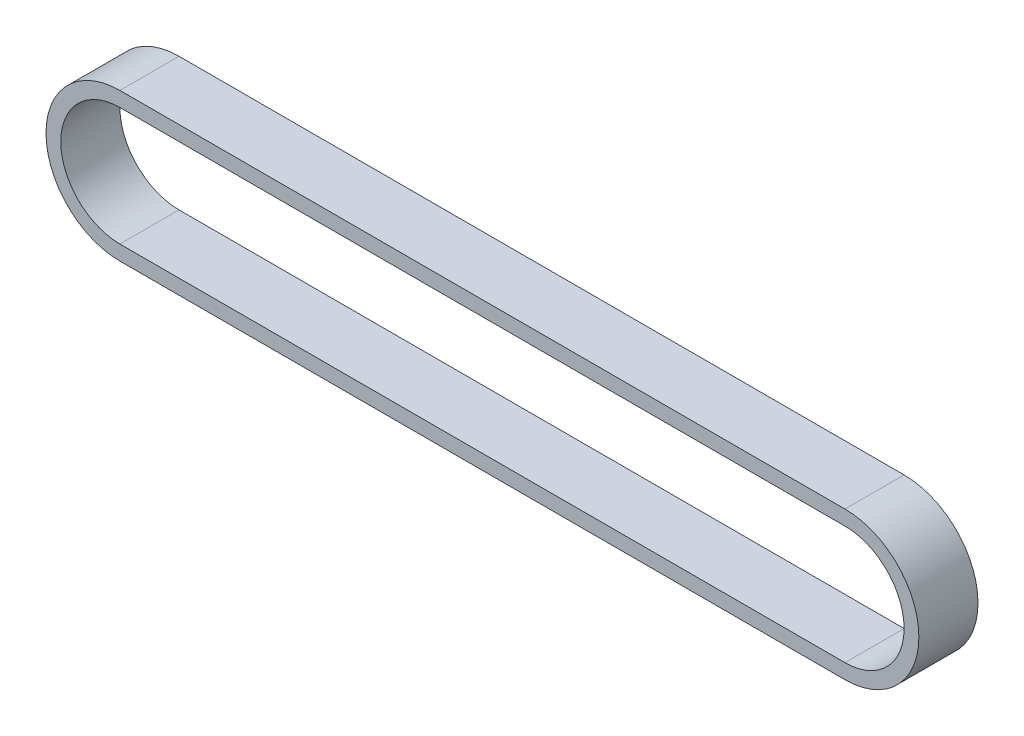
SolidWorks part; units mm, degrees
material "Rubber"
ref_plane "Front Plane" through (0, 0, 0) normal (0, 0, 1) x (1, 0, 0)
ref_plane "Top Plane" through (0, 0, 0) normal (0, 1, 0) x (1, 0, 0)
ref_plane "Right Plane" through (0, 0, 0) normal (1, 0, 0) x (0, 0, -1)
sketch "Sketch1" plane through (0, 0, 0) normal (0, 0, 1) x (1, 0, 0)
  line L0 (36.7898, 0) -> (-36.7898, 0)
  line L4 (-36.7898, -13) -> (36.7898, -13)
  arc A0 (-36.7898, 0) -> (-36.7898, -13) centre (-36.7898, -6.5) ccw
  arc A1 (36.7898, -13) -> (36.7898, 0) centre (36.7898, -6.5) ccw
  dimension "D1" = 6.5
  dimension "D2" = 188
extrude "Extrude-Thin1" add sketch "Sketch1" along normal mid plane 6 thin
